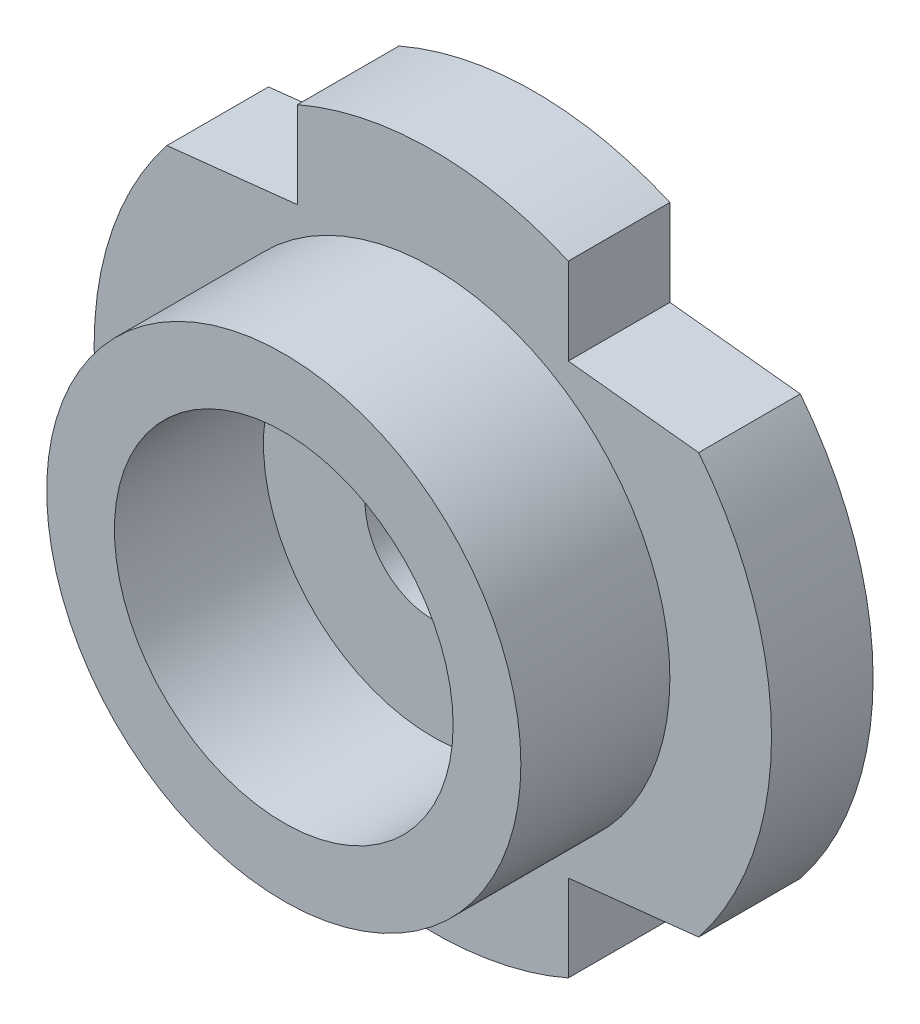
SolidWorks part; units mm, degrees
ref_plane "Front Plane" through (0, 0, 0) normal (0, 0, 1) x (1, 0, 0)
ref_plane "Top Plane" through (0, 0, 0) normal (0, 1, 0) x (1, 0, 0)
ref_plane "Right Plane" through (0, 0, 0) normal (1, 0, 0) x (0, 0, -1)
sketch "Sketch1" plane through (0, 0, 0) normal (0, 0, 1) x (1, 0, 0)
  line L0 (0, 0) -> (0, 10.3254) construction
  line L1 (0, 0) -> (16, 0) construction
  line L2 (2, 7.7586) -> (2, 3.3047)
  line L3 (2, 3.3047) -> (14.2143, 1.9885)
  line L4 (2, -3.3047) -> (14.2143, -1.9885)
  line L5 (2, -7.7586) -> (2, -3.3047)
  line L6 (-2, -7.7586) -> (-2, -3.3047)
  line L7 (-2, -3.3047) -> (-14.2143, -1.9885)
  line L8 (-2, 3.3047) -> (-14.2143, 1.9885)
  line L9 (-2, 7.7586) -> (-2, 3.3047)
  arc A0 (3.5, 0) -> (0, 3.5) centre (0, 0) ccw construction
  arc A1 (2.5, 0) -> (0, 2.5) centre (0, 0) ccw construction
  arc A2 (14.2143, -1.9885) -> (14.2143, 1.9885) centre (14, 0) ccw
  arc A3 (2, 7.7586) -> (-2, 7.7586) centre (0, 7.7586) ccw
  arc A4 (2, -7.7586) -> (-2, -7.7586) centre (0, -7.7586) cw
  arc A5 (-14.2143, -1.9885) -> (-14.2143, 1.9885) centre (-14, 0) cw
  dimension "D1" = 7
  dimension "D2" = 5
  dimension "D3" = 4
  dimension "D4" = 4
extrude "Boss-Extrude1" add sketch "Sketch1" along normal blind 1.5
sketch "Sketch2" plane through (0, 0, 1.5) normal (0, 0, 1) x (1, 0, 0)
  circle A0 centre (0, 0) radius 3.5
  circle A1 centre (0, 0) radius 2.5
  dimension "D1" = 7
  dimension "D2" = 5
extrude "Boss-Extrude2" add sketch "Sketch2" along normal blind 2.2
sketch "Sketch3" plane through (0, 0, 1.5) normal (0, 0, 1) x (1, 0, 0)
  circle A0 centre (0, 0) radius 1
  dimension "D1" = 2
extrude "Cut-Extrude1" cut sketch "Sketch3" against normal up to next
sketch "Sketch4" plane through (0, 0, 0) normal (0, 0, -1) x (-1, 0, 0)
  circle A0 centre (0, 0) radius 2.5
  dimension "D1" = 5
extrude "Cut-Extrude2" cut sketch "Sketch4" against normal blind 1
sketch "Sketch5" plane through (0, 0, 1.5) normal (0, 0, 1) x (1, 0, 0)
  circle A0 centre (0, 0) radius 5
  circle A1 centre (0, 0) radius 17.5
  dimension "D1" = 10
  dimension "D2" = 35
extrude "Cut-Extrude4" cut sketch "Sketch5" against normal up to next
